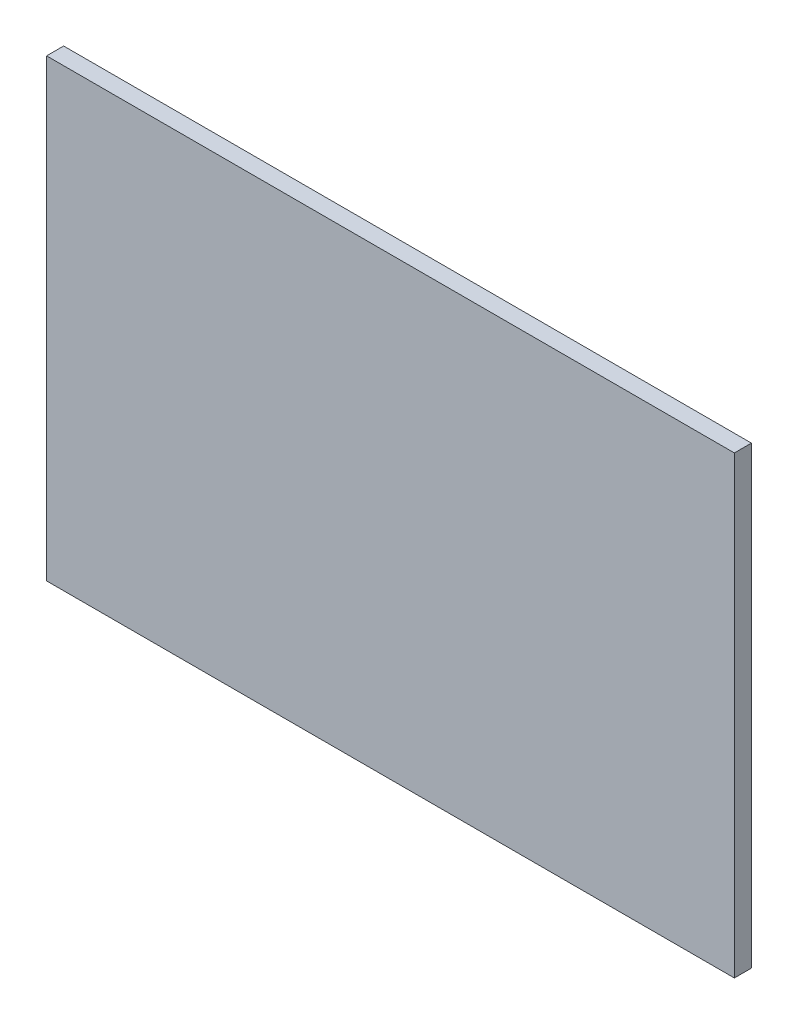
SolidWorks part; units mm, degrees
ref_plane "Plan de face" through (0, 0, 0) normal (0, 0, 1) x (1, 0, 0)
ref_plane "Plan de dessus" through (0, 0, 0) normal (0, 1, 0) x (1, 0, 0)
ref_plane "Plan de droite" through (0, 0, 0) normal (1, 0, 0) x (0, 0, -1)
sketch "Esquisse3" plane through (0, 0, 0) normal (0, 0, 1) x (1, 0, 0)
  line L1 (-56.5062, 29.1194) -> (64.4938, 29.1194)
  line L2 (-56.5062, 29.1194) -> (-56.5062, -50.8806)
  line L3 (-56.5062, -50.8806) -> (64.4938, -50.8806)
  line L4 (64.4938, 29.1194) -> (64.4938, -50.8806)
  dimension "D1" = 121
  dimension "D2" = 80
extrude "Boss.-Extru.2" add sketch "Esquisse3" along normal blind 3
